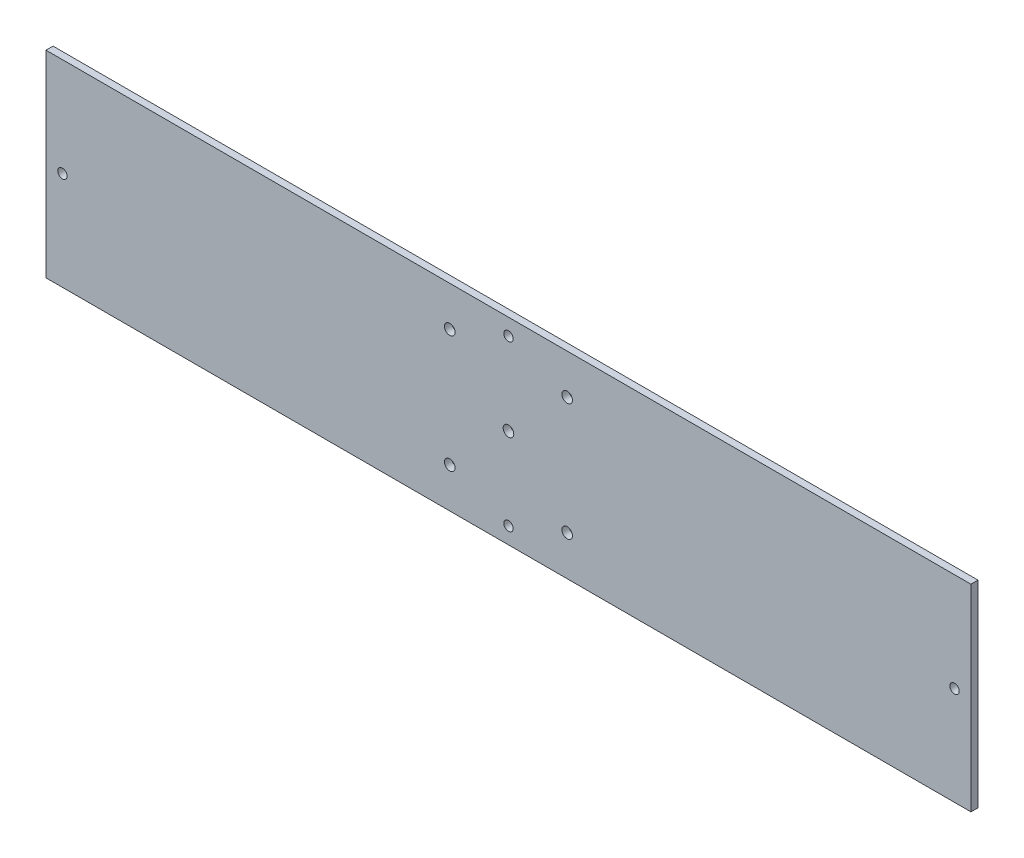
SolidWorks part; units mm, degrees
material "PMMA"
ref_plane "Piano frontale" through (0, 0, 0) normal (0, 0, 1) x (1, 0, 0)
ref_plane "Piano superiore" through (0, 0, 0) normal (0, 1, 0) x (1, 0, 0)
ref_plane "Piano destro" through (0, 0, 0) normal (1, 0, 0) x (0, 0, -1)
sketch "Schizzo1" plane through (0, 0, 0) normal (0, 0, 1) x (1, 0, 0)
  line L0 (0, 0) -> (0, 84)
  line L1 (0, 84) -> (394, 84)
  line L2 (394, 84) -> (394, 0)
  line L3 (394, 0) -> (0, 0)
  line L4 (0, 42) -> (394, 42) construction
  line L5 (197, 42) -> (197, 123.488) construction
  circle A0 centre (7, 42) radius 2
  circle A1 centre (197, 77) radius 2
  circle A2 centre (197, 7) radius 2
  circle A3 centre (387, 42) radius 2
  circle A4 centre (197, 42) radius 2.25
  circle A5 centre (172, 67) radius 2.25
  circle A6 centre (172, 17) radius 2.25
  circle A7 centre (222, 17) radius 2.25
  circle A8 centre (222, 67) radius 2.25
  point P46 (173, 42)
  point P94 (173, 42)
  dimension "D3" = 7
  dimension "D4" = 7
  dimension "D6" = 4
  dimension "D5" = 4.5
  dimension "D1" = 84
  dimension "D2" = 394
  dimension "D13" = 50
  dimension "D14" = 50
extrude "Estrusione-Estrusione1" add sketch "Schizzo1" along normal blind 3
